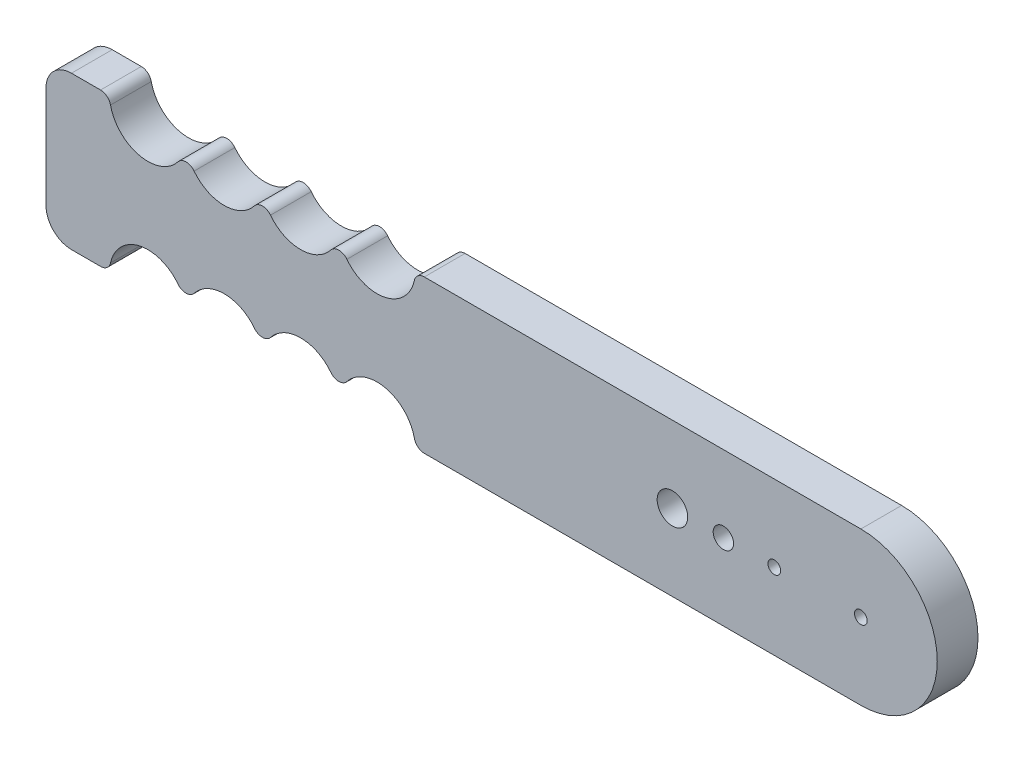
SolidWorks part; units mm, degrees
ref_plane "Front Plane" through (0, 0, 0) normal (0, 0, 1) x (1, 0, 0)
ref_plane "Top Plane" through (0, 0, 0) normal (0, 1, 0) x (1, 0, 0)
ref_plane "Right Plane" through (0, 0, 0) normal (1, 0, 0) x (0, 0, -1)
sketch "Sketch1" plane through (0, 0, 0) normal (0, 0, 1) x (1, 0, 0)
  line L0 (0, 0) -> (-100.1155, 0) construction
  line L1 (0, 15) -> (-87.5, 15)
  line L3 (0, -15) -> (-87.5, -15)
  line L4 (-160, 15) -> (-160, -15)
  line L5 (-147.5, 15) -> (-160, 15)
  line L6 (-147.5, -15) -> (-160, -15)
  arc A0 (0, -15) -> (0, 15) centre (0, 0) ccw
  arc A1 (-147.5, 15) -> (-132.5, 15) centre (-140, 15) ccw
  arc A2 (-132.5, 15) -> (-117.5, 15) centre (-125, 15) ccw
  arc A3 (-117.5, 15) -> (-102.5, 15) centre (-110, 15) ccw
  arc A4 (-102.5, 15) -> (-87.5, 15) centre (-95, 15) ccw
  arc A5 (-102.5, -15) -> (-87.5, -15) centre (-95, -15) cw
  arc A6 (-117.5, -15) -> (-102.5, -15) centre (-110, -15) cw
  arc A7 (-132.5, -15) -> (-117.5, -15) centre (-125, -15) cw
  arc A8 (-147.5, -15) -> (-132.5, -15) centre (-140, -15) cw
  circle A9 centre (0, 0) radius 1.25
  circle A10 centre (-17, 0) radius 1.25
  circle A11 centre (-37, 0) radius 3
  circle A12 centre (-27, 0) radius 2
  point P32 (-24.4228, 0)
  point P33 (-32.7129, 0)
  dimension "D1" = 30
  dimension "D3" = 15
  dimension "D5" = 20
  dimension "D4" = 2.5
  dimension "D6" = 2.5
  dimension "D7" = 17
  dimension "D8" = 6
  dimension "D9" = 4
  dimension "D11" = 10
  dimension "D2" = 160
  dimension "D10" = 10
extrude "Boss-Extrude1" add sketch "Sketch1" along normal blind 8
fillet "Fillet1" radius 5 2 edges at (-160, -15, 4) (-160, 15, 4)
fillet "Fillet2" radius 2 10 edges at (-87.5, -15, 4) (-102.5, -15, 4) (-117.5, -15, 4) (-132.5, -15, 4) (-147.5, -15, 4) (-87.5, 15, 4) (-102.5, 15, 4) (-117.5, 15, 4) (-132.5, 15, 4) (-147.5, 15, 4)
